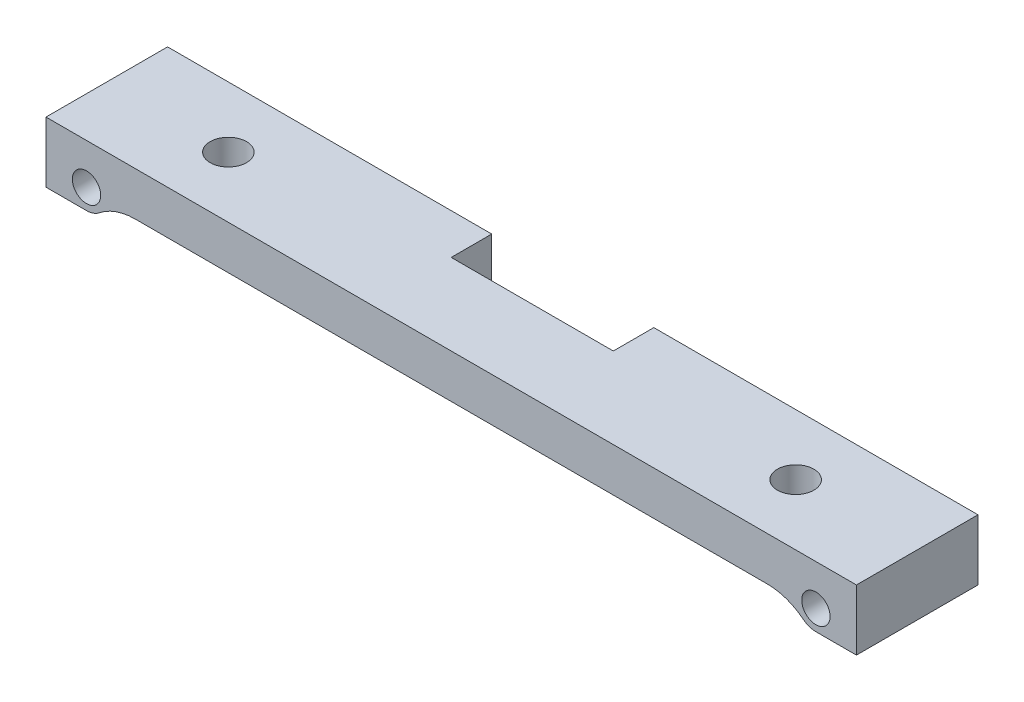
SolidWorks part; units mm, degrees
ref_plane "Front Plane" through (0, 0, 0) normal (0, 0, 1) x (1, 0, 0)
ref_plane "Top Plane" through (0, 0, 0) normal (0, 1, 0) x (1, 0, 0)
ref_plane "Right Plane" through (0, 0, 0) normal (1, 0, 0) x (0, 0, -1)
sketch "Sketch1" plane through (0, 0, 0) normal (0, 0, 1) x (1, 0, 0)
  line L0 (50, 57.5) -> (50, 65)
  line L1 (50, 65) -> (50, -65) construction
  line L2 (50, 65) -> (-50, 65)
  line L3 (-50, 65) -> (50, 65) construction
  line L6 (45, 60) -> (45, 52.2374) construction
  line L7 (50, 57.5) -> (45, 57.5)
  line L8 (44, 52.5) -> (39, 52.5) construction
  line L9 (39, 57.5) -> (39, 52.5) construction
  line L10 (39, 59.6047) -> (-39, 59.6047)
  line L11 (0, 59.6047) -> (0, 65) construction
  line L12 (-39, 57.5) -> (-39, 52.5) construction
  line L13 (-44, 52.5) -> (-39, 52.5) construction
  line L14 (-45, 60) -> (-45, 52.2374) construction
  line L15 (-50, 57.5) -> (-50, 65)
  line L16 (-50, 57.5) -> (-45, 57.5)
  circle A0 centre (45, 60) radius 1.75
  arc A2 (43.4383, 58.0478) -> (39, 59.6047) centre (39, 52.5) ccw
  arc A3 (45, 57.5) -> (43.4383, 58.0478) centre (45, 60) cw
  circle A4 centre (-45, 60) radius 1.75
  arc A5 (-45, 57.5) -> (-43.4383, 58.0478) centre (-45, 60) ccw
  arc A6 (-43.4383, 58.0478) -> (-39, 59.6047) centre (-39, 52.5) cw
  dimension "D1" = 3.5
  dimension "D2" = 2.5
extrude "Boss-Extrude1" add sketch "Sketch1" along normal blind 15
sketch "Sketch2" plane through (0, 65, 0) normal (0, 1, 0) x (1, 0, 0)
  line L0 (50, 0) -> (-50, 0) construction
  line L1 (50, -15) -> (50, 0) construction
  line L2 (0, -4.125) -> (0, 4.125) construction
  line L4 (10, 0) -> (-10, 0)
  line L5 (10, 0) -> (10, -5)
  line L6 (10, -5) -> (-10, -5)
  line L7 (-10, 0) -> (-10, -5)
  circle A0 centre (35, -7.5) radius 2.25
  circle A1 centre (-35, -7.5) radius 2.25
  dimension "D1" = 4.5
  dimension "D2" = 7.5
  dimension "D3" = 15
  dimension "D4" = 5
  dimension "D5" = 20
  dimension "D6" = 40
extrude "Cut-Extrude1" cut sketch "Sketch2" against normal blind 15
